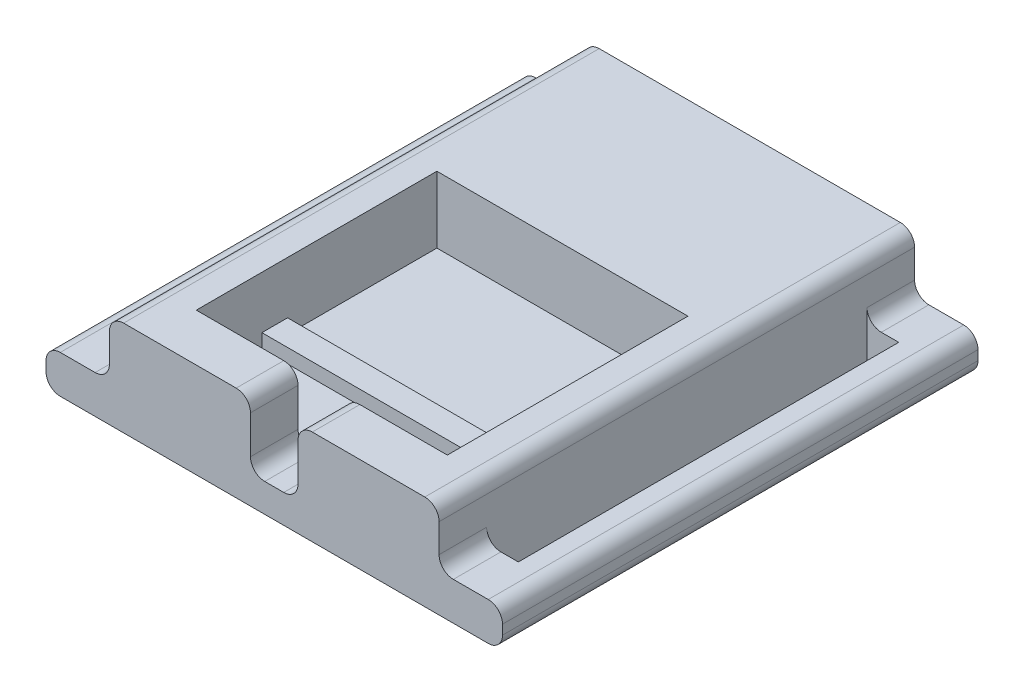
SolidWorks part; units mm, degrees
ref_plane "Front Plane" through (0, 0, 0) normal (0, 0, 1) x (1, 0, 0)
ref_plane "Top Plane" through (0, 0, 0) normal (0, 1, 0) x (1, 0, 0)
ref_plane "Right Plane" through (0, 0, 0) normal (1, 0, 0) x (0, 0, -1)
sketch "Sketch1" plane through (0, 0, 0) normal (0, 1, 0) x (1, 0, 0)
  line L1 (-17.5327, -11.5058) -> (30.4673, -11.5058)
  line L2 (-17.5327, -11.5058) -> (-17.5327, 38.4942)
  line L3 (-17.5327, 38.4942) -> (30.4673, 38.4942)
  line L4 (30.4673, -11.5058) -> (30.4673, 38.4942)
  line L5 (27.1343, -6.5058) -> (23.8003, -6.5058)
  line L6 (27.1343, -6.5058) -> (27.1343, 33.4942)
  line L7 (27.1343, 33.4942) -> (23.8003, 33.4942)
  line L8 (23.8003, -6.5058) -> (23.8003, 33.4942)
  line L9 (-14.1997, 33.4942) -> (-10.8657, 33.4942)
  line L10 (-14.1997, 33.4942) -> (-14.1997, -6.5058)
  line L11 (-14.1997, -6.5058) -> (-10.8657, -6.5058)
  line L12 (-10.8657, 33.4942) -> (-10.8657, -6.5058)
  dimension "D1" = 48
  dimension "D2" = 50
  dimension "D3" = 40
  dimension "D4" = 5
  dimension "D5" = 3.333
  dimension "D6" = 3.334
  dimension "D7" = 3.334
  dimension "D8" = 5
  dimension "D9" = 40
  dimension "D10" = 3.333
extrude "Boss-Extrude1" add sketch "Sketch1" along normal blind 4
sketch "Sketch2" plane through (0, 4, 0) normal (0, 1, 0) x (1, 0, 0)
  line L6 (-17.5327, -11.5058) -> (30.4673, -11.5058) construction
  line L7 (-10.8657, -11.5058) -> (-6.7317, -11.5058)
  line L8 (-10.8657, -11.5058) -> (-10.8657, 38.4942)
  line L9 (-10.8657, 38.4942) -> (-6.7317, 38.4942)
  line L10 (-6.7317, -11.5058) -> (-6.7317, 38.4942)
  line L11 (30.4673, 38.4942) -> (-17.5327, 38.4942) construction
  line L12 (-10.8657, -6.5058) -> (-10.8657, 33.4942) construction
  dimension "D1" = 4.134
  dimension "D2" = 0
extrude "Boss-Extrude2" add sketch "Sketch2" along normal blind 6
sketch "Sketch8" plane through (0, 4, 0) normal (0, 1, 0) x (1, 0, 0)
  line L0 (30.4673, 38.4942) -> (-6.7317, 38.4942) construction
  line L1 (23.8003, 38.4942) -> (19.6663, 38.4942)
  line L2 (23.8003, 38.4942) -> (23.8003, -11.5058)
  line L3 (23.8003, -11.5058) -> (19.6663, -11.5058)
  line L4 (19.6663, 38.4942) -> (19.6663, -11.5058)
  line L5 (-6.7317, -11.5058) -> (30.4673, -11.5058) construction
  line L6 (23.8003, 33.4942) -> (23.8003, -6.5058) construction
  dimension "D1" = 4.134
  dimension "D2" = 0
extrude "Boss-Extrude6" add sketch "Sketch8" along normal blind 6
sketch "Sketch9" plane through (0, 4, 0) normal (0, 1, 0) x (1, 0, 0)
  line L0 (19.6663, 38.4942) -> (-6.7317, 38.4942) construction
  line L1 (19.6663, 38.4942) -> (-6.7317, 38.4942)
  line L2 (19.6663, 38.4942) -> (19.6663, 18.7942)
  line L3 (19.6663, 18.7942) -> (-6.7317, 18.7942)
  line L4 (-6.7317, 38.4942) -> (-6.7317, 18.7942)
  line L5 (-6.7317, -11.5058) -> (-6.7317, 38.4942) construction
  dimension "D1" = 0
  dimension "D2" = 19.7
extrude "Boss-Extrude7" add sketch "Sketch9" along normal blind 6
sketch "Sketch10" plane through (0, 4, 0) normal (0, 1, 0) x (1, 0, 0)
  line L0 (19.6663, 18.7942) -> (19.6663, -11.5058) construction
  line L1 (-6.7317, -11.5058) -> (19.6663, -11.5058)
  line L2 (-6.7317, -11.5058) -> (-6.7317, -6.5058)
  line L3 (-6.7317, -6.5058) -> (19.6663, -6.5058)
  line L4 (19.6663, -11.5058) -> (19.6663, -6.5058)
  dimension "D1" = 5
extrude "Boss-Extrude8" add sketch "Sketch10" along normal blind 6
sketch "Sketch11" plane through (0, 10, 0) normal (0, 1, 0) x (1, 0, 0)
  line L0 (19.6663, -6.5058) -> (-6.7317, -6.5058) construction
  line L1 (3.9683, -6.5058) -> (8.9683, -6.5058)
  line L2 (3.9683, -6.5058) -> (3.9683, -11.5058)
  line L3 (3.9683, -11.5058) -> (8.9683, -11.5058)
  line L4 (8.9683, -6.5058) -> (8.9683, -11.5058)
  line L5 (-10.8657, -11.5058) -> (23.8003, -11.5058) construction
  line L6 (-10.8657, -6.5058) -> (-10.8657, -11.5058) construction
  dimension "D1" = 5
  dimension "D2" = 14.834
extrude "Cut-Extrude1" cut sketch "Sketch11" against normal blind 7
fillet "Fillet9" radius 1.5 1 edges at (-10.8657, 4, 9.0058)
fillet "Fillet10" radius 1.5 1 edges at (-10.8657, 4, -35.9942)
fillet "Fillet13" radius 1.5 1 edges at (23.8003, 4, -35.9942)
fillet "Fillet14" radius 1.5 1 edges at (23.8003, 4, 9.0058)
fillet "Fillet15" radius 1.5 8 edges at (-17.5327, 0, -13.4942) (-17.5327, 4, -13.4942) (-10.8657, 10, -13.4942) (3.9683, 10, 9.0058) (8.9683, 10, 9.0058) (23.8003, 10, -13.4942) (30.4673, 4, -13.4942) (30.4673, 0, -13.4942)
sketch "Sketch12" plane through (0, 4, 0) normal (0, 1, 0) x (1, 0, 0)
  line L1 (19.6663, 18.7942) -> (-6.7317, 18.7942)
  line L2 (19.6663, 18.7942) -> (19.6663, -6.5058)
  line L3 (19.6663, -6.5058) -> (-6.7317, -6.5058)
  line L4 (-6.7317, 18.7942) -> (-6.7317, -6.5058)
extrude "Cut-Extrude2" cut sketch "Sketch12" against normal blind 1
sketch "Sketch13" plane through (0, 3, 0) normal (0, 1, 0) x (1, 0, 0)
  line L8 (-6.7317, 18.7942) -> (-6.7317, -6.5058) construction
  line L9 (-6.7317, 3.0942) -> (19.6663, 3.0942)
  line L10 (-6.7317, 3.0942) -> (-6.7317, 0.3942)
  line L11 (-6.7317, 0.3942) -> (19.6663, 0.3942)
  line L12 (19.6663, 3.0942) -> (19.6663, 0.3942)
  line L13 (19.6663, 18.7942) -> (19.6663, -6.5058) construction
  line L15 (8.9683, -6.5058) -> (19.6663, -6.5058) construction
  dimension "D1" = 2.7
  dimension "D2" = 0
  dimension "D3" = 6.9
extrude "Boss-Extrude10" add sketch "Sketch13" along normal blind 1.5
fillet "Fillet18" radius 1.5 1 edges at (3.9683, 3, 9.0058)
fillet "Fillet19" radius 1.5 1 edges at (8.9683, 3, 9.0058)
